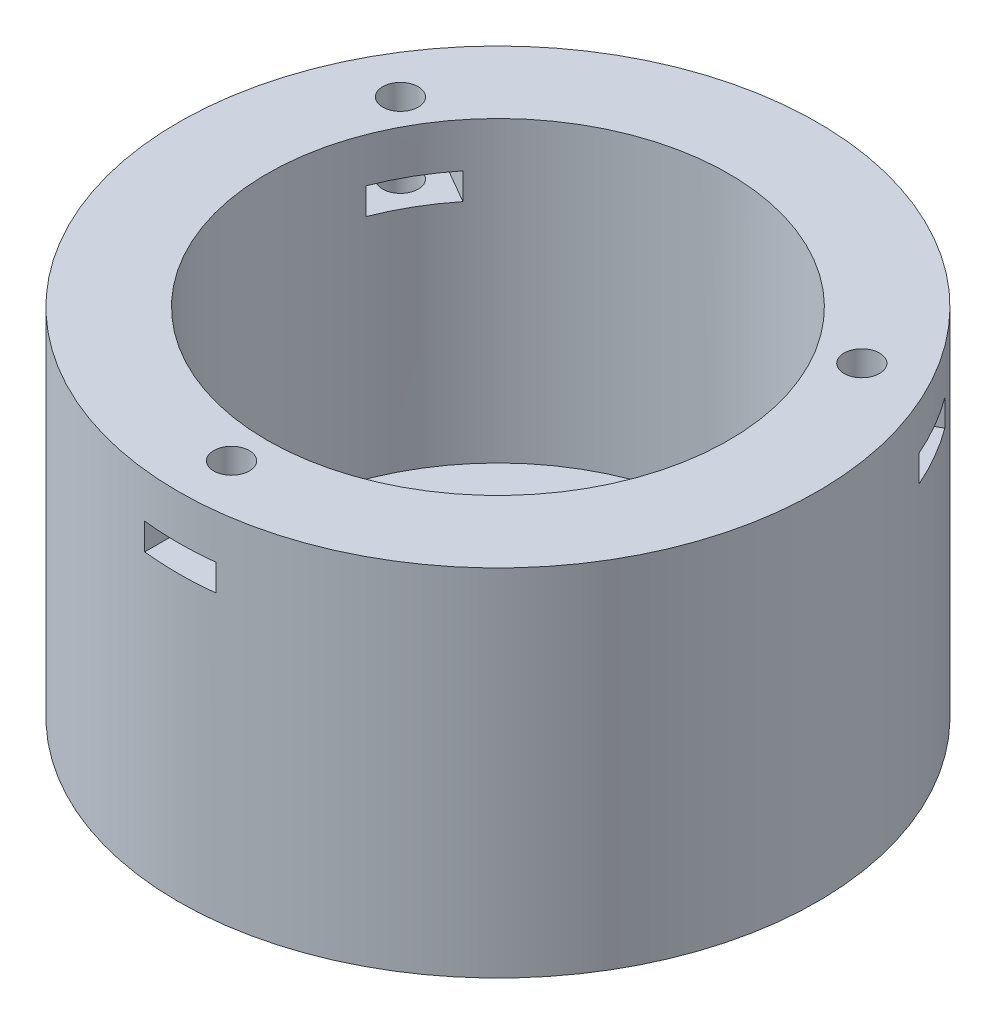
SolidWorks part; units mm, degrees
ref_plane "Front Plane" through (0, 0, 0) normal (0, 0, 1) x (1, 0, 0)
ref_plane "Top Plane" through (0, 0, 0) normal (0, 1, 0) x (1, 0, 0)
ref_plane "Right Plane" through (0, 0, 0) normal (1, 0, 0) x (0, 0, -1)
sketch "Sketch1" plane through (0, 0, 0) normal (0, 1, 0) x (1, 0, 0)
  circle A0 centre (0, 0) radius 57.15
  dimension "D1" = 114.3
extrude "Boss-Extrude1" add sketch "Sketch1" along normal blind 63.5
sketch "Sketch2" plane through (0, 63.5, 0) normal (0, 1, 0) x (1, 0, 0)
  circle A0 centre (0, 0) radius 41.275
  dimension "D1" = 82.55
extrude "Cut-Extrude1" cut sketch "Sketch2" against normal offset from surface (53.34 mm away) 10.16 up to face at (0, 0, 57.15)
sketch "Sketch3" plane through (0, 63.5, 0) normal (0, 1, 0) x (1, 0, 0)
  circle A0 centre (0, 0) radius 47.625 construction
  dimension "D1" = 95.25
hole_wizard "1/4 (0.25) Diameter Hole4" positions "Sketch5" profile "Sketch6" hole size "1/4" standard "ANSI Inch"
sketch "Sketch5" plane through (0, 63.5, 0) normal (0, 1, 0) x (1, 0, 0)
  line L0 (-41.2445, 23.8125) -> (41.2445, 23.8125) construction
  line L1 (41.2445, 23.8125) -> (0, -47.625) construction
  line L2 (0, -47.625) -> (-41.2445, 23.8125) construction
  circle A0 centre (0, 0) radius 47.625 construction
  point P0 (-41.2445, 23.8125)
  point P2 (0, -47.625)
  point P4 (41.2445, 23.8125)
  dimension "D1" = 82.4889
sketch "Sketch6" plane through (-41.2445, 63.5, -23.8125) normal (1, 0, 0) x (0, 0, 1)
  line L0 (0, 0) -> (0, 27.3077)
  line L1 (0, 27.3077) -> (3.175, 25.4)
  line L2 (3.175, 25.4) -> (3.175, 0)
  line L5 (3.175, 0) -> (0, 0)
  line L10 (0, 27.3077) -> (-3.175, 25.4) construction
  line L11 (0, -6.35) -> (0, 107.95) construction
  dimension "Hole Dia." = 6.35
  dimension "Hole Depth" = 25.4
  dimension "Drill Angle" = 118
sketch "Sketch7" plane through (0, 0, 0) normal (0, 0, 1) x (1, 0, 0)
  circle A0 centre (0, 15.24) radius 3.81
  dimension "D1" = 7.62
  dimension "D2" = 15.24
extrude "Cut-Extrude2" cut sketch "Sketch7" against normal through all
hole_wizard "Ø4.0mm Dowel Hole1" positions "3DSketch1" profile "Sketch8" hole size "Ø4.0" standard "ANSI Metric" end condition through all
sketch3d "3DSketch1"
  line L0 (-5, 0, 15.9385) -> (5, 0, -33.5615) construction
  line L2 (5, 0, 15.9385) -> (-5, 0, -33.5615) construction
  point P0 (-5, 0, 15.9385)
  point P2 (5, 0, 15.9385)
  point P4 (5, 0, -33.5615)
  point P6 (-5, 0, -33.5615)
  point P29 (0, 0, -8.8115)
  dimension "D1" = 10
  dimension "D2" = 49.5
sketch "Sketch8" plane through (-5, 0, 15.9385) normal (1, 0, 0) x (0, 0, -1)
  line L0 (0, 0) -> (0, 63.5)
  line L1 (0, 63.5) -> (2, 63.5)
  line L2 (2, 63.5) -> (2, 0)
  line L5 (2, 0) -> (0, 0)
  line L11 (0, -6.35) -> (0, 107.95) construction
  dimension "Thru Hole Dia." = 4
  dimension "Thru Hole Depth" = 63.5
sketch "Sketch9" plane through (0, 0, 0) normal (0, -1, 0) x (1, 0, 0)
  line L1 (-1.5, 12.4385) -> (-8.5, 12.4385)
  line L2 (-1.5, 12.4385) -> (-1.5, 19.4385)
  line L3 (-1.5, 19.4385) -> (-8.5, 19.4385)
  line L4 (-8.5, 12.4385) -> (-8.5, 19.4385)
  line L5 (-1.5, 12.4385) -> (-8.5, 19.4385) construction
  line L6 (-1.5, 19.4385) -> (-8.5, 12.4385) construction
  line L11 (8.5, 12.4385) -> (1.5, 12.4385)
  line L12 (8.5, 12.4385) -> (8.5, 19.4385)
  line L13 (8.5, -37.0615) -> (1.5, -37.0615)
  line L14 (8.5, -37.0615) -> (8.5, -30.0615)
  line L15 (8.5, -30.0615) -> (1.5, -30.0615)
  line L16 (1.5, -37.0615) -> (1.5, -30.0615)
  line L17 (8.5, -37.0615) -> (1.5, -30.0615) construction
  line L18 (8.5, -30.0615) -> (1.5, -37.0615) construction
  line L19 (-1.5, -37.0615) -> (-8.5, -37.0615)
  line L20 (-1.5, -37.0615) -> (-1.5, -30.0615)
  line L21 (-1.5, -30.0615) -> (-8.5, -30.0615)
  line L22 (-8.5, -37.0615) -> (-8.5, -30.0615)
  line L23 (-1.5, -37.0615) -> (-8.5, -30.0615) construction
  line L24 (-1.5, -30.0615) -> (-8.5, -37.0615) construction
  line L25 (8.5, 19.4385) -> (1.5, 19.4385)
  line L26 (1.5, 12.4385) -> (1.5, 19.4385)
  line L27 (8.5, 12.4385) -> (1.5, 19.4385) construction
  line L28 (8.5, 19.4385) -> (1.5, 12.4385) construction
  point P0 (-5, 15.9385)
  point P7 (5, 15.9385)
  point P12 (5, -33.5615)
  point P18 (-5, -33.5615)
  dimension "D1" = 7
  dimension "D2" = 7
extrude "Cut-Extrude3" cut sketch "Sketch9" against normal blind 3.5
ref_plane "Plane1" through (0, 50.8, 0) normal (0, 1, 0) x (1, 0, 0)
sketch "Sketch12" plane through (0, 50.8, 0) normal (0, 1, 0) x (1, 0, 0)
  line L1 (-38.4946, 14.8925) -> (-32.1446, 25.8911)
  line L3 (-48.6424, 35.4161) -> (-54.9924, 24.4175)
  line L5 (48.6424, 35.4161) -> (54.9924, 24.4175)
  line L7 (38.4946, 14.8925) -> (32.1446, 25.8911)
  line L8 (-48.6424, 35.4161) -> (-32.1446, 25.8911)
  line L13 (6.35, -59.8336) -> (-6.35, -59.8336)
  line L14 (6.35, -59.8336) -> (6.35, -40.7836)
  line L15 (6.35, -40.7836) -> (-6.35, -40.7836)
  line L16 (-6.35, -59.8336) -> (-6.35, -40.7836)
  line L19 (-54.9924, 24.4175) -> (-38.4946, 14.8925)
  line L20 (48.6424, 35.4161) -> (32.1446, 25.8911)
  line L21 (54.9924, 24.4175) -> (38.4946, 14.8925)
  line L22 (0, 0) -> (51.8174, 29.9168) construction
  line L23 (0, 0) -> (-51.8174, 29.9168)
  circle A1 centre (0, 0) radius 41.275 construction
  circle A2 centre (0, 0) radius 41.275 construction
  point P14 (0, -47.625)
  point P15 (0, -47.625)
  dimension "D1" = 12.7
  dimension "D2" = 19.05
extrude "Cut-Extrude4" cut sketch "Sketch12" along normal blind 4.7625 contours L1 L23 L3 L19 | L23 L1 L8 L3 | L7 L22 L5 L20 | L22 L7 L21 L5 | L16 L13 L14 L15
